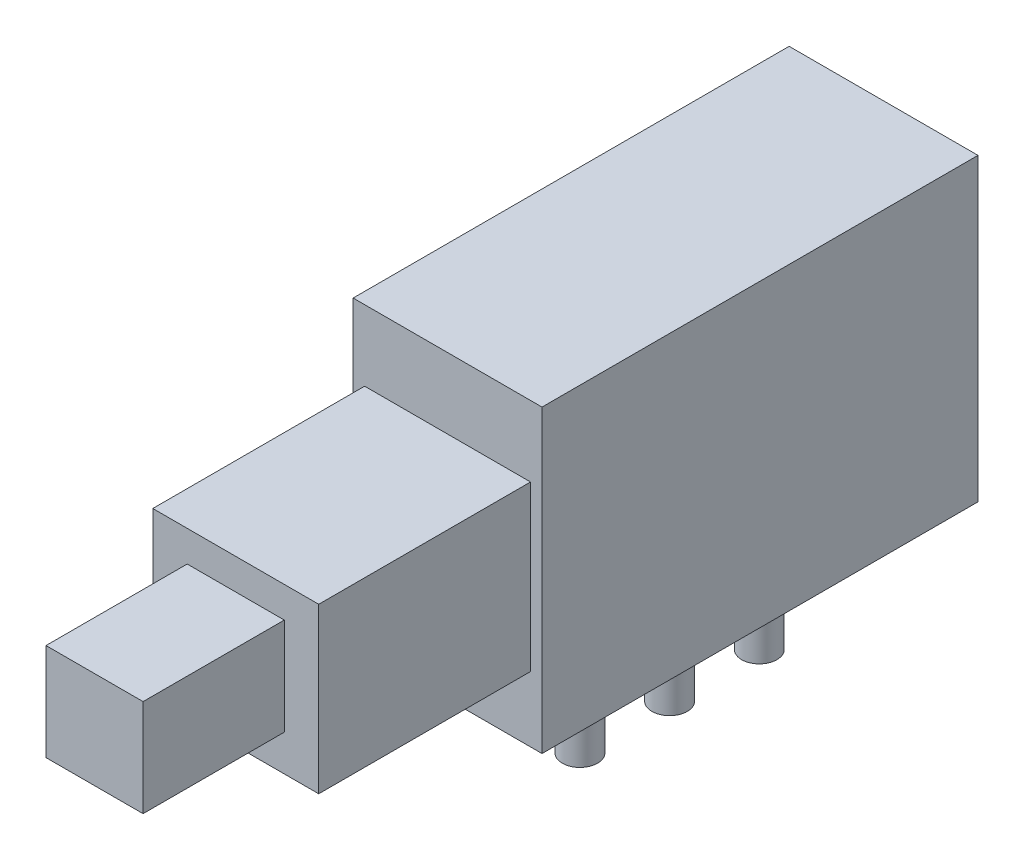
SolidWorks part; units mm, degrees
ref_plane "Front Plane" through (0, 0, 0) normal (0, 0, 1) x (1, 0, 0)
ref_plane "Top Plane" through (0, 0, 0) normal (0, 1, 0) x (1, 0, 0)
ref_plane "Right Plane" through (0, 0, 0) normal (1, 0, 0) x (0, 0, -1)
sketch "Sketch1" plane through (0, 0, 0) normal (0, 0, 1) x (1, 0, 0)
  line L1 (-2.675, -4.25) -> (2.675, -4.25)
  line L2 (-2.675, -4.25) -> (-2.675, 4.25)
  line L3 (-2.675, 4.25) -> (2.675, 4.25)
  line L4 (2.675, -4.25) -> (2.675, 4.25)
  line L5 (-2.675, -4.25) -> (2.675, 4.25) construction
  line L6 (-2.675, 4.25) -> (2.675, -4.25) construction
  point P0 (0, 0)
  dimension "D1" = 8.5
  dimension "D2" = 5.35
extrude "Boss-Extrude1" add sketch "Sketch1" along normal blind 12.35 contours L3 L4 L1 L2
sketch "Sketch2" plane through (0, 0, 12.35) normal (0, 0, 1) x (1, 0, 0)
  line L1 (-1.375, -1.375) -> (1.375, -1.375)
  line L2 (-1.375, -1.375) -> (-1.375, 1.375)
  line L3 (-1.375, 1.375) -> (1.375, 1.375)
  line L4 (1.375, -1.375) -> (1.375, 1.375)
  line L5 (-1.375, -1.375) -> (1.375, 1.375) construction
  line L6 (-1.375, 1.375) -> (1.375, -1.375) construction
  point P0 (0, 0)
  dimension "D1" = 2.75
  dimension "D2" = 2.75
extrude "Boss-Extrude2" add sketch "Sketch2" along normal blind 10 contours L3 L4 L1 L2
sketch "Sketch4" plane through (0, 0, 12.35) normal (0, 0, 1) x (1, 0, 0)
  line L0 (0, 2.25) -> (0, 0) construction
  line L1 (-2.35, 2.25) -> (2.35, 2.25)
  line L2 (-2.35, 2.25) -> (-2.35, -2.4)
  line L3 (-2.35, -2.4) -> (2.35, -2.4)
  line L4 (2.35, 2.25) -> (2.35, -2.4)
  line L5 (-2.675, 4.25) -> (2.675, 4.25) construction
  dimension "D1" = 4.7
  dimension "D2" = 4.65
  dimension "D3" = 2
extrude "Boss-Extrude4" add sketch "Sketch4" along normal blind 6 contours L1 L4 L3 L2
sketch "Sketch3" plane through (0, -4.25, 0) normal (0, -1, 0) x (1, 0, 0)
  line L0 (-2.675, 12.35) -> (2.675, 12.35) construction
  line L1 (0, 6.06) -> (0, 8.6) construction
  line L3 (0, 0) -> (0, 3.52) construction
  line L4 (-2.675, 0) -> (2.675, 0) construction
  circle A0 centre (0, 8.6) radius 0.5
  circle A4 centre (0, 6.06) radius 0.5
  circle A5 centre (0, 3.52) radius 0.5
  circle A6 centre (7.62, 8.6) radius 0.5 [skipped]
  circle A7 centre (7.62, 6.06) radius 0.5 [skipped]
  circle A8 centre (7.62, 3.52) radius 0.5 [skipped]
  dimension "D3" = 1
  dimension "D4" = 2.54
  dimension "D5" = 3.75
  dimension "D1" = 2
  dimension "D2" = 3
extrude "Boss-Extrude3" add sketch "Sketch3" along normal blind 3.2
